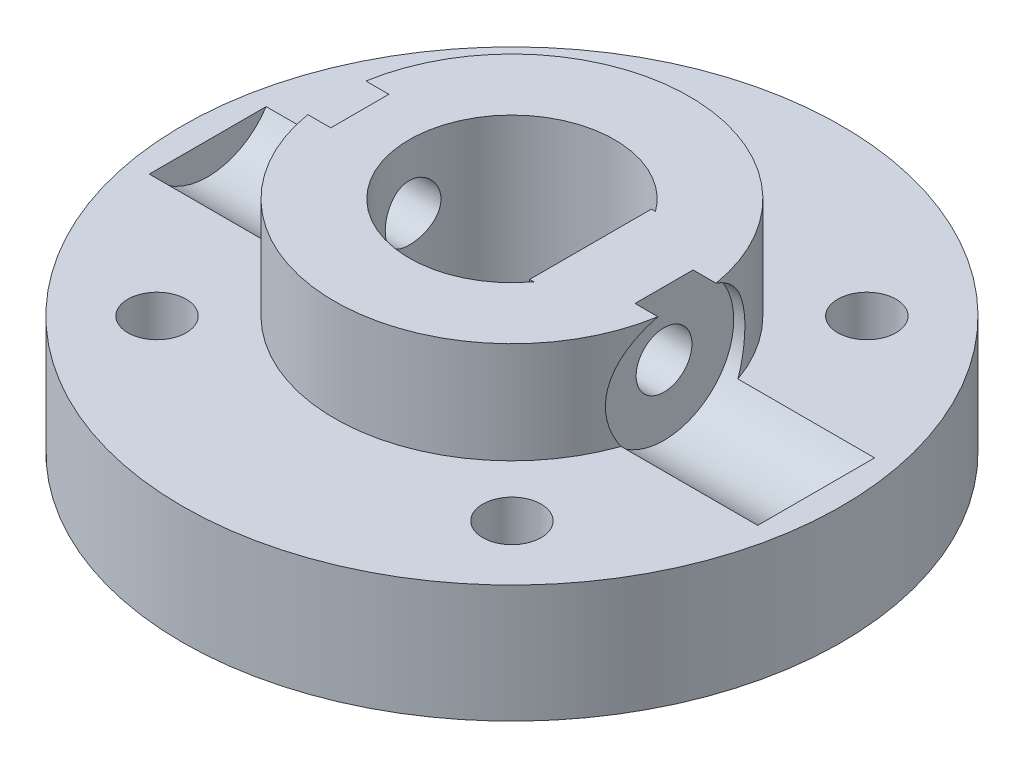
SolidWorks part; units mm, degrees
ref_plane "Front Plane" through (0, 0, 0) normal (0, 0, 1) x (1, 0, 0)
ref_plane "Top Plane" through (0, 0, 0) normal (0, 1, 0) x (1, 0, 0)
ref_plane "Right Plane" through (0, 0, 0) normal (1, 0, 0) x (0, 0, -1)
sketch "Stock_horn_drive_flange_profile" plane through (0, 0, 0) normal (0, 1, 0) x (1, 0, 0)
  circle A0 centre (0, 0) radius 13
  circle A1 centre (0, 0) radius 4.05
  dimension "D1" = 26
  dimension "D2" = 8.1
extrude "Stock_horn_drive_flange" add sketch "Stock_horn_drive_flange_profile" along normal blind 3 from offset 41
sketch "D_coupling_ring_profile" plane through (0, 0, 0) normal (0, 1, 0) x (1, 0, 0)
  circle A0 centre (0, 0) radius 7
  circle A1 centre (0, 0) radius 4.05
  dimension "D1" = 14
  dimension "D2" = 8.1
extrude "D_coupling_ring" add sketch "D_coupling_ring_profile" along normal blind 4 from offset 44
sketch "D_key_land_profile" plane through (0, 0, 0) normal (0, 1, 0) x (1, 0, 0)
  line L1 (3.1, -2.4) -> (6, -2.4)
  line L2 (3.1, -2.4) -> (3.1, 2.4)
  line L3 (3.1, 2.4) -> (6, 2.4)
  line L4 (6, -2.4) -> (6, 2.4)
  dimension "D1" = 2.9
  dimension "D2" = 4.8
  dimension "D3" = 3.1
  dimension "D4" = 2.4
extrude "D_key_land" add sketch "D_key_land_profile" along normal blind 4 from offset 44
sketch "Captured_horn_key_boss_profile" plane through (0, 0, 0) normal (0, 1, 0) x (1, 0, 0)
  circle A0 centre (0, 0) radius 13
  dimension "D1" = 26
extrude "Captured_horn_key_boss" add sketch "Captured_horn_key_boss_profile" along normal blind 1.65 from offset 39.35
sketch "Stock_horn_pocket_Hub" plane through (0, 0, 0) normal (0, 1, 0) x (1, 0, 0)
  circle A0 centre (0, 0) radius 3.55
  dimension "D1" = 7.1
extrude "Key_pocket_Hub" cut sketch "Stock_horn_pocket_Hub" along normal blind 1.65 from offset 39.35
sketch "Stock_horn_pocket_Horizontal" plane through (0, 0, 0) normal (0, 1, 0) x (1, 0, 0)
  line L1 (-8.15, -2.1) -> (8.15, -2.1)
  line L2 (-8.15, -2.1) -> (-8.15, 2.1)
  line L3 (-8.15, 2.1) -> (8.15, 2.1)
  line L4 (8.15, -2.1) -> (8.15, 2.1)
  dimension "D1" = 16.3
  dimension "D2" = 4.2
  dimension "D3" = 8.15
  dimension "D4" = 2.1
extrude "Key_pocket_Horizontal" cut sketch "Stock_horn_pocket_Horizontal" along normal blind 1.65 from offset 39.35
sketch "Stock_horn_pocket_Vertical" plane through (0, 0, 0) normal (0, 1, 0) x (1, 0, 0)
  line L1 (-2.1, -8.15) -> (2.1, -8.15)
  line L2 (-2.1, -8.15) -> (-2.1, 8.15)
  line L3 (-2.1, 8.15) -> (2.1, 8.15)
  line L4 (2.1, -8.15) -> (2.1, 8.15)
  dimension "D1" = 4.2
  dimension "D2" = 16.3
  dimension "D3" = 2.1
  dimension "D4" = 8.15
extrude "Key_pocket_Vertical" cut sketch "Stock_horn_pocket_Vertical" along normal blind 1.65 from offset 39.35
sketch "Stock_horn_pocket_Rounded_tips" plane through (0, 0, 0) normal (0, 1, 0) x (1, 0, 0)
  circle A0 centre (8.15, 0) radius 2.1
  circle A1 centre (-8.15, 0) radius 2.1
  circle A2 centre (0, 8.15) radius 2.1
  circle A3 centre (0, -8.15) radius 2.1
  dimension "D1" = 4.2
  dimension "D2" = 4.2
  dimension "D3" = 4.2
  dimension "D4" = 4.2
  dimension "D5" = 8.15
  dimension "D6" = 8.15
  dimension "D7" = 8.15
  dimension "D8" = 8.15
extrude "Key_pocket_Rounded_tips" cut sketch "Stock_horn_pocket_Rounded_tips" along normal blind 1.65 from offset 39.35
sketch "Unmodified_horn_capture_M2_profile" plane through (0, 0, 0) normal (0, 1, 0) x (1, 0, 0)
  circle A0 centre (7, 7) radius 1.15
  circle A1 centre (-7, 7) radius 1.15
  circle A2 centre (-7, -7) radius 1.15
  circle A3 centre (7, -7) radius 1.15
  dimension "D1" = 2.3
  dimension "D2" = 2.3
  dimension "D3" = 2.3
  dimension "D4" = 2.3
  dimension "D5" = 7
  dimension "D6" = 7
  dimension "D7" = 7
  dimension "D8" = 7
extrude "Unmodified_horn_capture_M2" cut sketch "Unmodified_horn_capture_M2_profile" along normal through all from offset 50
sketch "Horn_center_hub_clearance" plane through (0, 0, 0) normal (0, 1, 0) x (1, 0, 0)
  circle A0 centre (0, 0) radius 4
  dimension "D1" = 8
extrude "Hub_clearance_in_key_boss_only" cut sketch "Horn_center_hub_clearance" along normal blind 1.65 from offset 39.35
sketch "Yaw_positive_retention_crossbolt_profile" plane through (0, 0, 0) normal (1, 0, 0) x (0, 0, -1)
  circle A0 centre (0, 45.5) radius 1.1
  dimension "D1" = 2.2
  dimension "D2" = 45.5
extrude "Yaw_positive_retention_crossbolt" cut sketch "Yaw_positive_retention_crossbolt_profile" along normal through all from offset 10
sketch "Crossbolt_flat_seat_-12" plane through (0, 0, 0) normal (1, 0, 0) x (0, 0, -1)
  circle A0 centre (0, 45.5) radius 2.75
  dimension "D1" = 5.5
  dimension "D2" = 45.5
extrude "Crossbolt_flat_seat_cut_-12" cut sketch "Crossbolt_flat_seat_-12" along normal blind 6 from offset 12
sketch "Crossbolt_flat_seat_6" plane through (0, 0, 0) normal (1, 0, 0) x (0, 0, -1)
  circle A0 centre (0, 45.5) radius 2.75
  dimension "D1" = 5.5
  dimension "D2" = 45.5
extrude "Crossbolt_flat_seat_cut_6" cut sketch "Crossbolt_flat_seat_6" along normal blind 6 from offset 6
